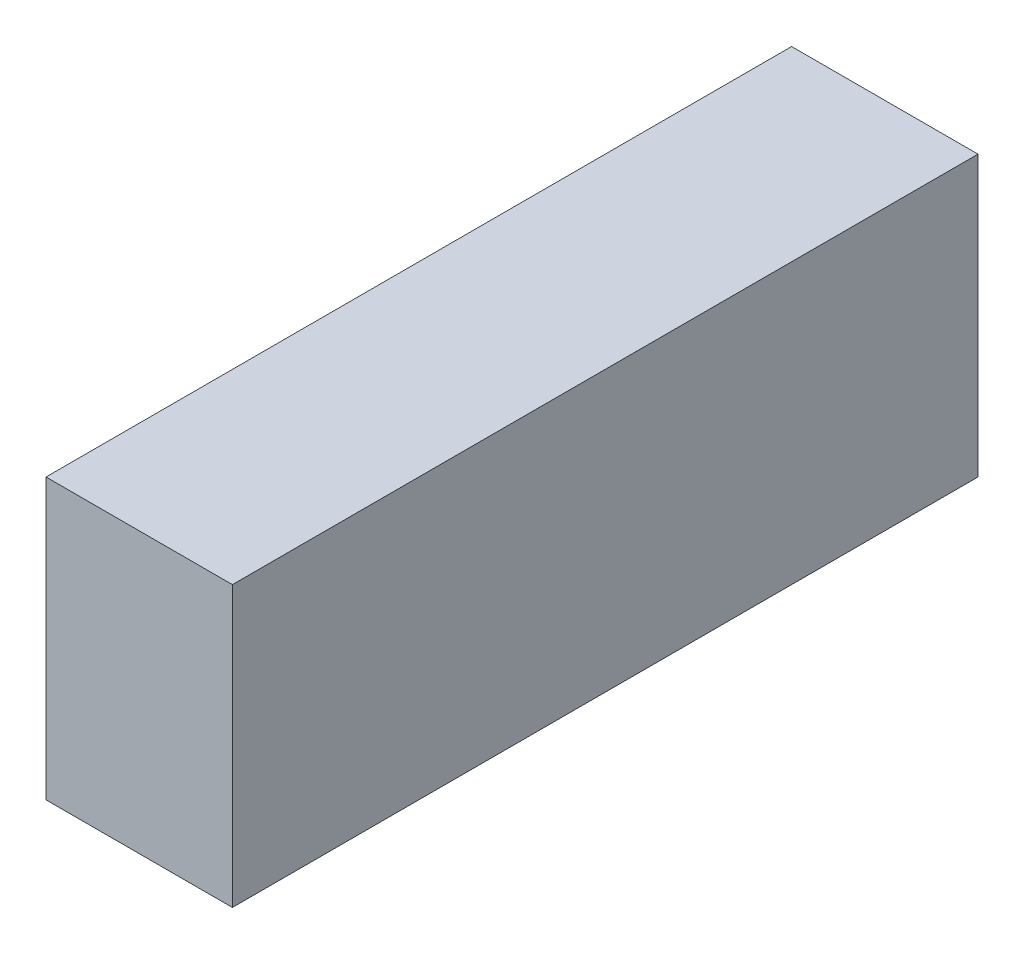
SolidWorks part; units mm, degrees
ref_plane "Front Plane" through (0, 0, 0) normal (0, 0, 1) x (1, 0, 0)
ref_plane "Top Plane" through (0, 0, 0) normal (0, 1, 0) x (1, 0, 0)
ref_plane "Right Plane" through (0, 0, 0) normal (1, 0, 0) x (0, 0, -1)
other "Configuration Table"
sketch "Sketch1" plane through (0, 0, 0) normal (0, 0, 1) x (1, 0, 0)
  line L1 (2, 29) -> (12, 29)
  line L2 (2, 29) -> (2, 44)
  line L3 (2, 44) -> (12, 44)
  line L4 (12, 29) -> (12, 44)
extrude "CEK_1L_kayis_baglanti_pabucu_1" add sketch "Sketch1" against normal blind 40 from offset 40 separate body
